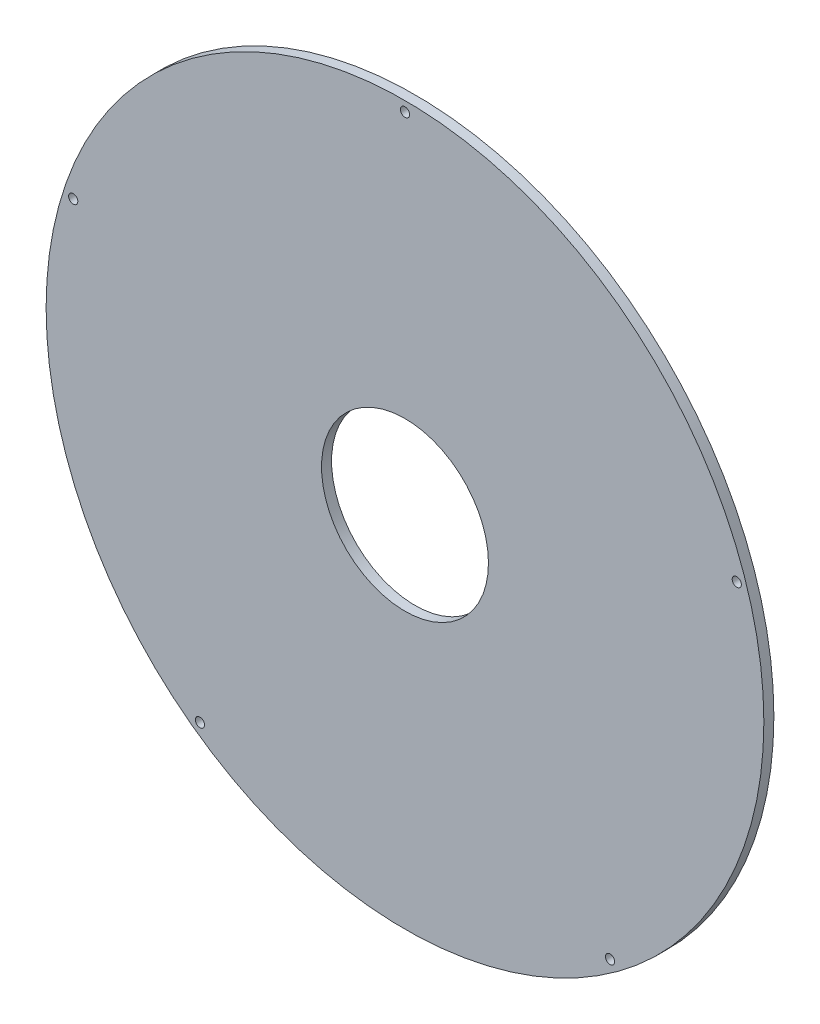
SolidWorks part; units mm, degrees
ref_plane "Front Plane" through (0, 0, 0) normal (0, 0, 1) x (1, 0, 0)
ref_plane "Top Plane" through (0, 0, 0) normal (0, 1, 0) x (1, 0, 0)
ref_plane "Right Plane" through (0, 0, 0) normal (1, 0, 0) x (0, 0, -1)
sketch "Sketch1" plane through (0, 0, 0) normal (0, 0, 1) x (1, 0, 0)
  circle A0 centre (0, 0) radius 215
  circle A1 centre (0, 0) radius 50
extrude "Lid" add sketch "Sketch1" along normal blind 6
sketch "Sketch2" plane through (0, 0, 0) normal (0, 0, 1) x (1, 0, 0)
  circle A0 centre (198.7708, 64.5846) radius 2.75
  circle A1 centre (0, 209) radius 2.75
  circle A2 centre (-198.7708, 64.5846) radius 2.75
  circle A3 centre (-122.8471, -169.0846) radius 2.75
  circle A4 centre (122.8471, -169.0846) radius 2.75
extrude "Rod_holes" cut sketch "Sketch2" along normal blind 6
